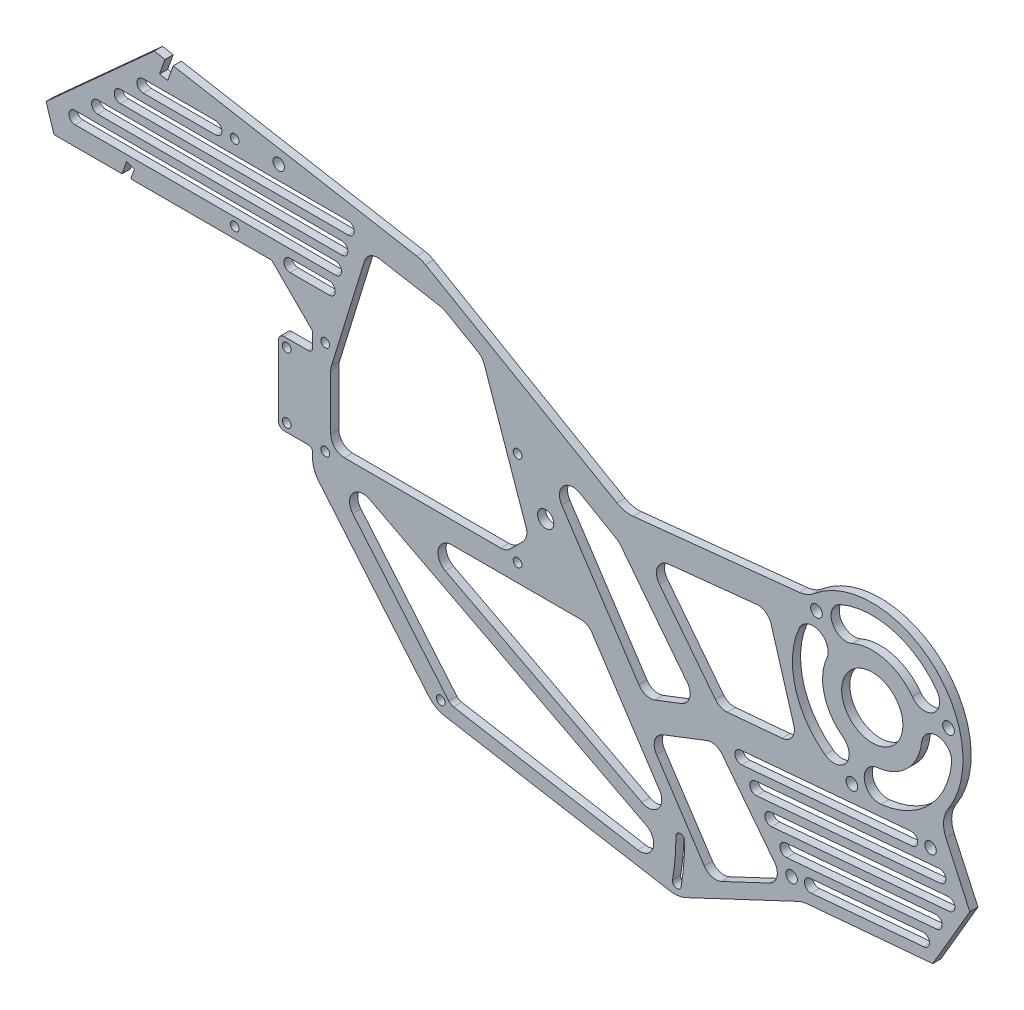
SolidWorks part; units mm, degrees
ref_plane "Front Plane" through (0, 0, 0) normal (0, 0, 1) x (1, 0, 0)
ref_plane "Top Plane" through (0, 0, 0) normal (0, 1, 0) x (1, 0, 0)
ref_plane "Right Plane" through (0, 0, 0) normal (1, 0, 0) x (0, 0, -1)
sketch "Sketch2" plane through (0, 0, 0) normal (0, 0, 1) x (1, 0, 0)
  line L0 (53.0727, 40.6) -> (-51.5431, 101) construction
  line L1 (53.0727, 40.6) -> (120.5529, 47.6) construction
  line L2 (53.0727, 40.6) -> (-21.5794, 83.7005)
  line L3 (53.0727, 40.6) -> (120.5529, 47.6)
  line L4 (-63.0431, 34) -> (-72.0431, 34) construction
  line L5 (-74.0431, 32) -> (-74.0431, 6) construction
  line L6 (-72.0431, 4) -> (-63.0431, 4) construction
  line L7 (-63.0431, 34) -> (-72.0431, 34)
  line L8 (-74.0431, 32) -> (-74.0431, 6)
  line L9 (-72.0431, 4) -> (-63.0431, 4)
  line L10 (-61.5431, 2.5) -> (-61.5431, -3) construction
  line L11 (-61.5431, 2.5) -> (-61.5431, -3)
  line L12 (-61.5431, 56) -> (-61.5431, 35.5) construction
  line L13 (-61.5431, 56) -> (-61.5431, 35.5)
  line L14 (-124.7453, 56) -> (-61.5431, 56) construction
  line L15 (-156.5431, 56) -> (-61.5431, 56)
  line L16 (-156.5431, 56) -> (-159.4878, 65.0628)
  line L17 (-159.4878, 65.0628) -> (-119.69, 101)
  line L18 (-119.69, 101) -> (-21.5794, 83.7005)
  line L19 (168.6964, 1.4596) -> (179.9678, -23.0752)
  line L20 (179.9678, -23.0752) -> (166.3352, -46.3808)
  line L22 (-124.7453, 56) -> (-127.69, 65.0628) construction
  line L23 (166.3352, -46.3808) -> (118.4161, -50.5732)
  line L24 (118.4161, -50.5732) -> (72.8599, -72.0315)
  line L25 (72.8599, -72.0315) -> (-16.548, -56.6231)
  line L26 (-16.548, -56.6231) -> (-61.5431, -3)
  line L27 (-51.5431, 101) -> (-119.69, 101) construction
  line L28 (-61.5431, -3) -> (-31.4636, -3) construction
  line L29 (73.5747, -52.93) -> (-14.4253, -52.93) construction
  line L33 (-42.7431, 62.05) -> (-42.7431, 39.5) construction
  line L34 (-41.9931, 62.8) -> (-1.0931, 62.8) construction
  line L35 (-0.3431, 62.05) -> (-0.3431, 39.5) construction
  line L36 (8.2869, 39.5) -> (-0.3431, 39.5) construction
  line L37 (-42.7431, 39.5) -> (-51.3731, 39.5) construction
  line L38 (-52.8731, 10) -> (-52.8731, 38) construction
  line L39 (9.7869, 10) -> (9.7869, 38) construction
  line L40 (8.2869, 8.5) -> (-51.3731, 8.5) construction
  line L41 (-42.7431, 62.05) -> (-42.7431, 39.5)
  line L42 (-41.9931, 62.8) -> (-1.0931, 62.8)
  line L43 (-0.3431, 62.05) -> (-0.3431, 39.5)
  line L44 (8.2869, 39.5) -> (-0.3431, 39.5)
  line L45 (-42.7431, 39.5) -> (-51.3731, 39.5)
  line L46 (-52.8731, 10) -> (-52.8731, 38)
  line L47 (9.7869, 10) -> (9.7869, 38)
  line L48 (8.2869, 8.5) -> (-51.3731, 8.5)
  arc A0 (177.4669, 23.9998) -> (120.5529, 47.6) centre (144.1169, 24) ccw construction
  arc A1 (168.6964, 1.4596) -> (120.5529, 47.6) centre (144.1169, 24) ccw
  arc A2 (-72.0431, 34) -> (-74.0431, 32) centre (-72.0431, 32) ccw construction
  arc A3 (-74.0431, 6) -> (-72.0431, 4) centre (-72.0431, 6) ccw construction
  arc A4 (-72.0431, 34) -> (-74.0431, 32) centre (-72.0431, 32) ccw
  arc A5 (-74.0431, 6) -> (-72.0431, 4) centre (-72.0431, 6) ccw
  arc A6 (-61.5431, 2.5) -> (-63.0431, 4) centre (-63.0431, 2.5) ccw construction
  arc A7 (-61.5431, 2.5) -> (-63.0431, 4) centre (-63.0431, 2.5) ccw
  arc A8 (-63.0431, 34) -> (-61.5431, 35.5) centre (-63.0431, 35.5) ccw construction
  arc A9 (-63.0431, 34) -> (-61.5431, 35.5) centre (-63.0431, 35.5) ccw
  circle A10 centre (-56.8731, 39.6) radius 1.6 construction
  circle A11 centre (13.7869, 39.6) radius 1.6 construction
  circle A12 centre (13.7869, 5) radius 1.6 construction
  circle A13 centre (-56.8731, 5) radius 1.6 construction
  circle A14 centre (-56.8731, 39.6) radius 1.6
  circle A15 centre (13.7869, 39.6) radius 1.6
  circle A16 centre (13.7869, 5) radius 1.6
  circle A17 centre (-56.8731, 5) radius 1.6
  circle A18 centre (-71.0431, 31) radius 1.6 construction
  circle A19 centre (-71.0431, 7) radius 1.6 construction
  circle A22 centre (24.1169, 24) radius 3 construction
  circle A23 centre (24.1169, 24) radius 3
  arc A24 (166.3088, -44.4468) -> (169.7736, -48.3119) centre (169.1616, -45.375) ccw construction
  arc A25 (-0.3431, 62.05) -> (-1.0931, 62.8) centre (-0.3431, 62.8) ccw construction
  arc A26 (-41.9931, 62.8) -> (-42.7431, 62.05) centre (-42.7431, 62.8) ccw construction
  arc A27 (-51.3731, 39.5) -> (-52.8731, 38) centre (-51.3731, 38) ccw construction
  circle A32 centre (123.6108, 44.5061) radius 2.15 construction
  circle A33 centre (172.1287, 31.5058) radius 2.15 construction
  circle A34 centre (136.6111, -4.0118) radius 2.15 construction
  circle A35 centre (123.6108, 44.5061) radius 2.15
  circle A36 centre (172.1287, 31.5058) radius 2.15
  circle A37 centre (136.6111, -4.0118) radius 2.15
  arc A38 (126.757, 0.3344) -> (133.3224, 9.2846) centre (130.0397, 4.8095) ccw construction
  arc A39 (127.4109, 31.3467) -> (133.3224, 9.2846) centre (144.1169, 24) ccw construction
  arc A40 (117.25, 35.8151) -> (126.757, 0.3344) centre (144.1169, 24) ccw construction
  arc A41 (127.4109, 31.3467) -> (117.25, 35.8151) centre (122.3305, 33.5809) ccw construction
  arc A42 (132.3018, 50.8668) -> (136.7702, 40.706) centre (134.536, 45.7864) ccw construction
  arc A43 (167.7824, 41.3598) -> (132.3018, 50.8668) centre (144.1169, 24) ccw construction
  arc A44 (158.8323, 34.7944) -> (136.7702, 40.706) centre (144.1169, 24) ccw construction
  arc A45 (158.8323, 34.7944) -> (167.7824, 41.3598) centre (163.3073, 38.0771) ccw construction
  circle A46 centre (144.1169, 24) radius 11.25 construction
  arc A47 (173.2918, 20.7987) -> (162.258, 22.0094) centre (167.7749, 21.4041) ccw construction
  arc A48 (146.1075, 5.8589) -> (162.258, 22.0094) centre (144.1169, 24) ccw construction
  arc A49 (147.3182, -5.1749) -> (173.2918, 20.7987) centre (144.1169, 24) ccw construction
  arc A50 (146.1075, 5.8589) -> (147.3182, -5.1749) centre (146.7128, 0.342) ccw construction
  arc A51 (126.757, 0.3344) -> (133.3224, 9.2846) centre (130.0397, 4.8095) ccw
  arc A52 (127.4109, 31.3467) -> (133.3224, 9.2846) centre (144.1169, 24) ccw
  arc A53 (117.25, 35.8151) -> (126.757, 0.3344) centre (144.1169, 24) ccw
  arc A54 (127.4109, 31.3467) -> (117.25, 35.8151) centre (122.3305, 33.5809) ccw
  arc A55 (132.3018, 50.8668) -> (136.7702, 40.706) centre (134.536, 45.7864) ccw
  arc A56 (167.7824, 41.3598) -> (132.3018, 50.8668) centre (144.1169, 24) ccw
  arc A57 (158.8323, 34.7944) -> (136.7702, 40.706) centre (144.1169, 24) ccw
  arc A58 (158.8323, 34.7944) -> (167.7824, 41.3598) centre (163.3073, 38.0771) ccw
  circle A59 centre (144.1169, 24) radius 11.25
  arc A60 (173.2918, 20.7987) -> (162.258, 22.0094) centre (167.7749, 21.4041) ccw
  arc A61 (146.1075, 5.8589) -> (162.258, 22.0094) centre (144.1169, 24) ccw
  arc A62 (147.3182, -5.1749) -> (173.2918, 20.7987) centre (144.1169, 24) ccw
  arc A63 (146.1075, 5.8589) -> (147.3182, -5.1749) centre (146.7128, 0.342) ccw
  circle A64 centre (-14.4253, -52.93) radius 1.6
  arc A65 (70.7196, -67.6037) -> (71.9747, -52.93) centre (-14.4253, -52.93) ccw
  arc A66 (73.8731, -68.1471) -> (75.1747, -52.93) centre (-14.4253, -52.93) ccw
  arc A67 (73.8731, -68.1471) -> (70.7196, -67.6037) centre (72.2963, -67.8754) cw
  arc A68 (75.1747, -52.93) -> (71.9747, -52.93) centre (73.5747, -52.93) ccw
  circle A69 centre (-71.0431, 31) radius 1.6
  circle A70 centre (-71.0431, 7) radius 1.6
  arc A71 (-52.8731, 10) -> (-51.3731, 8.5) centre (-51.3731, 10) ccw construction
  arc A72 (9.7869, 38) -> (8.2869, 39.5) centre (8.2869, 38) ccw construction
  arc A73 (8.2869, 8.5) -> (9.7869, 10) centre (8.2869, 10) ccw construction
  arc A74 (-0.3431, 62.05) -> (-1.0931, 62.8) centre (-0.3431, 62.8) ccw
  arc A75 (-41.9931, 62.8) -> (-42.7431, 62.05) centre (-42.7431, 62.8) ccw
  arc A76 (-51.3731, 39.5) -> (-52.8731, 38) centre (-51.3731, 38) ccw
  arc A77 (-52.8731, 10) -> (-51.3731, 8.5) centre (-51.3731, 10) ccw
  arc A78 (9.7869, 38) -> (8.2869, 39.5) centre (8.2869, 38) ccw
  arc A79 (8.2869, 8.5) -> (9.7869, 10) centre (8.2869, 10) ccw
  dimension "D3" = 1.6
  dimension "D6" = 3.2
  dimension "D7" = 4
  dimension "D8" = 4
  dimension "D1" = 88
  dimension "D2" = 15
  dimension "D4" = 95
  dimension "D5" = 10
  dimension "D9" = 4
  dimension "D10" = 4
  dimension "D11" = 50
  dimension "D12" = 70
  dimension "D13" = 35
  dimension "D14" = 5
  dimension "D15" = 27
  dimension "D16" = 55
extrude "Boss-Extrude1" add sketch "Sketch2" against normal blind 3
sketch "Sketch3" plane through (0, 0, 0) normal (0, 0, 1) x (1, 0, 0)
  line L0 (57.9603, -64.39) -> (-9.7599, -52.7193)
  line L1 (-11.5485, -51.6912) -> (-46.7716, -9.7139)
  line L2 (-40.6328, -2.0648) -> (61.1181, -55.0275)
  line L3 (-16.548, -56.6231) -> (72.8599, -72.0315) construction
  line L4 (-61.5431, -3) -> (-16.548, -56.6231) construction
  line L6 (65.9453, -41.3432) -> (41.192, -3.7503)
  line L7 (37.016, -1.5) -> (-10.4535, -1.5)
  line L8 (-12.7621, -10.9352) -> (59.4608, -48.5281)
  line L9 (-72.0431, 4) -> (-63.0431, 4) construction
  line L10 (11.0945, 7.9645) -> (15.7264, 12.5963)
  line L11 (16.9131, 17.7751) -> (1.5105, 62.0375)
  line L12 (-0.7118, 64.7243) -> (-12.7713, 71.6869)
  line L14 (-54.8731, 31.748) -> (-54.8731, 11.5)
  line L15 (-49.8731, 6.5) -> (7.559, 6.5)
  line L16 (88.7195, -59.0342) -> (106.3629, -50.7236)
  line L17 (108.1762, -43.1269) -> (88.9982, -18.5166)
  line L18 (83.255, -16.925) -> (67.1921, -23.1206)
  line L19 (64.8154, -30.5354) -> (82.4129, -57.2606)
  line L20 (64.3088, -13.5147) -> (74.0097, -9.7729)
  line L21 (76.1542, -2.0345) -> (51.5925, 29.4845)
  line L22 (50.1486, 30.7413) -> (36.6662, 38.5253)
  line L23 (29.9902, 31.4455) -> (58.3334, -11.5994)
  line L24 (110.9315, -2.3425) -> (90.802, -4.1036)
  line L25 (86.4223, -2.196) -> (65.8664, 24.1824)
  line L26 (69.2945, 32.2291) -> (101.6316, 35.5836)
  line L27 (106.9405, 32.0339) -> (115.4276, 3.4604)
  line L28 (72.8599, -72.0315) -> (118.4161, -50.5732) construction
  line L29 (118.4161, -50.5732) -> (166.3352, -46.3808) construction
  line L30 (-51.3731, 8.5) -> (8.2869, 8.5) construction
  line L31 (-52.8731, 38) -> (-52.8731, 10) construction
  line L32 (-14.4031, 72.2808) -> (-36.8286, 76.235)
  line L33 (-42.4757, 72.7818) -> (-54.6519, 33.2187)
  line L34 (53.0727, 40.6) -> (-21.5794, 83.7005) construction
  line L35 (-21.5794, 83.7005) -> (-119.69, 101) construction
  line L36 (120.5529, 47.6) -> (53.0727, 40.6) construction
  line L37 (162.8894, -40.3884) -> (121.4652, -44.0125) construction
  line L38 (163.0872, -42.6497) -> (121.663, -46.2738)
  line L39 (162.6915, -38.1271) -> (121.2673, -41.7512)
  line L40 (167.5555, -32.4114) -> (112.4569, -37.2319) construction
  line L41 (167.7533, -34.6728) -> (112.6547, -39.4933)
  line L42 (167.3576, -30.1501) -> (112.2591, -34.9706)
  line L43 (172.2216, -24.4345) -> (106.9353, -30.1463) construction
  line L44 (172.4194, -26.6958) -> (107.1332, -32.4076)
  line L45 (172.0237, -22.1732) -> (106.7375, -27.885)
  line L46 (168.8788, -17.1583) -> (101.4137, -23.0607) construction
  line L47 (169.0766, -19.4196) -> (101.6116, -25.322)
  line L48 (168.681, -14.897) -> (101.2159, -20.7994)
  line L49 (142.1773, -42.2004) -> (141.5201, -34.6892) construction
  line L50 (141.5201, -34.6892) -> (140.863, -27.1781) construction
  line L51 (140.863, -27.1781) -> (140.2058, -19.6669) construction
  line L52 (166.3352, -46.3808) -> (179.9678, -23.0752) construction
  line L53 (112.4569, -37.2319) -> (101.4137, -23.0607) construction
  line L54 (106.9353, -30.1463) -> (101.4138, -34.449) construction
  line L55 (158.5627, -10.4922) -> (95.8921, -15.9751) construction
  line L56 (158.7605, -12.7535) -> (96.09, -18.2364)
  line L57 (158.3648, -8.2309) -> (95.6943, -13.7138)
  line L58 (140.2058, -19.6669) -> (139.5487, -12.1557) construction
  line L59 (-10.4535, -6.5) -> (-42.9414, -6.5) construction
  line L60 (121.4652, -44.0125) -> (114.4918, -44.6226) construction
  line L61 (165.536, -9.8821) -> (172.2216, -24.4345) construction
  line L62 (179.9678, -23.0752) -> (168.6964, 1.4596) construction
  line L63 (104.1746, -32.2977) -> (118.4161, -50.5732) construction
  arc A0 (9.7869, 38) -> (8.2869, 39.5) centre (8.2869, 38) ccw construction
  arc A1 (-0.3431, 62.05) -> (-1.0931, 62.8) centre (-0.3431, 62.8) ccw construction
  circle A2 centre (13.7869, 5) radius 1.6 construction
  circle A3 centre (-56.8731, 39.6) radius 1.6 construction
  arc A5 (117.25, 35.8151) -> (126.757, 0.3344) centre (144.1169, 24) ccw construction
  arc A6 (61.1181, -55.0275) -> (57.9603, -64.39) centre (58.8095, -59.4627) cw
  arc A7 (163.0872, -42.6497) -> (162.6915, -38.1271) centre (162.8894, -40.3884) ccw
  arc A8 (121.2673, -41.7512) -> (121.663, -46.2738) centre (121.4652, -44.0125) ccw
  arc A9 (167.7533, -34.6728) -> (167.3576, -30.1501) centre (167.5555, -32.4114) ccw
  arc A10 (112.2591, -34.9706) -> (112.6547, -39.4933) centre (112.4569, -37.2319) ccw
  arc A11 (172.4194, -26.6958) -> (172.0237, -22.1732) centre (172.2216, -24.4345) ccw
  arc A12 (106.7375, -27.885) -> (107.1332, -32.4076) centre (106.9353, -30.1463) ccw
  arc A13 (169.0766, -19.4196) -> (168.681, -14.897) centre (168.8788, -17.1583) ccw
  arc A14 (101.2159, -20.7994) -> (101.6116, -25.322) centre (101.4137, -23.0607) ccw
  arc A15 (65.9453, -41.3432) -> (59.4608, -48.5281) centre (61.7693, -44.0929) cw
  arc A16 (158.7605, -12.7535) -> (158.3648, -8.2309) centre (158.5627, -10.4922) ccw
  arc A17 (95.6943, -13.7138) -> (96.09, -18.2364) centre (95.8921, -15.9751) ccw
  arc A18 (168.6964, 1.4596) -> (120.5529, 47.6) centre (144.1169, 24) ccw construction
  circle A19 centre (165.536, -9.8821) radius 2.1
  circle A20 centre (24.1169, 24) radius 3 construction
  arc A21 (-54.8731, 11.5) -> (-49.8731, 6.5) centre (-49.8731, 11.5) ccw
  arc A22 (-54.6519, 33.2187) -> (-54.8731, 31.748) centre (-49.8731, 31.748) ccw
  arc A23 (-36.8286, 76.235) -> (-42.4757, 72.7818) centre (-37.6969, 71.311) ccw
  arc A24 (-12.7713, 71.6869) -> (-14.4031, 72.2808) centre (-15.2713, 67.3568) ccw
  arc A25 (1.5105, 62.0375) -> (-0.7118, 64.7243) centre (-3.2118, 60.3942) ccw
  arc A26 (15.7264, 12.5963) -> (16.9131, 17.7751) centre (12.1908, 16.1318) ccw
  arc A27 (11.0945, 7.9645) -> (7.559, 6.5) centre (7.559, 11.5) cw
  arc A43 (-9.7599, -52.7193) -> (-11.5485, -51.6912) centre (-9.2504, -49.7628) cw
  circle A47 centre (114.4918, -44.6226) radius 2.1
  arc A48 (-12.7621, -10.9352) -> (-10.4535, -1.5) centre (-10.4535, -6.5) cw
  arc A49 (-46.7716, -9.7139) -> (-40.6328, -2.0648) centre (-42.9414, -6.5) cw
  arc A50 (106.3629, -50.7236) -> (108.1762, -43.1269) centre (104.2323, -46.2003) ccw
  arc A51 (88.7195, -59.0342) -> (82.4129, -57.2606) centre (86.5889, -54.5109) cw
  arc A52 (67.1921, -23.1206) -> (64.8154, -30.5354) centre (68.9914, -27.7856) ccw
  arc A53 (83.255, -16.925) -> (88.9982, -18.5166) centre (85.0543, -21.59) cw
  arc A54 (86.4223, -2.196) -> (90.802, -4.1036) centre (90.3662, 0.8773) ccw
  arc A55 (110.9315, -2.3425) -> (115.4276, 3.4604) centre (110.4957, 2.6384) ccw
  arc A56 (101.6316, 35.5836) -> (106.9405, 32.0339) centre (102.1475, 30.6102) cw
  arc A57 (69.2945, 32.2291) -> (65.8664, 24.1824) centre (69.8104, 27.2558) ccw
  arc A58 (74.0097, -9.7729) -> (76.1542, -2.0345) centre (72.2103, -5.1079) ccw
  arc A59 (37.016, -1.5) -> (41.192, -3.7503) centre (37.016, -6.5) cw
  arc A60 (58.3334, -11.5994) -> (64.3088, -13.5147) centre (62.5094, -8.8496) ccw
  arc A61 (50.1486, 30.7413) -> (51.5925, 29.4845) centre (47.6486, 26.4111) cw
  arc A62 (36.6662, 38.5253) -> (29.9902, 31.4455) centre (34.1662, 34.1952) ccw
  arc A63 (75.1747, -52.93) -> (71.9747, -52.93) centre (73.5747, -52.93) ccw construction
  point P7 (117.9785, -44.3176)
  point P42 (142.1773, -42.2004)
  point P55 (140.0062, -34.8217)
  point P69 (139.5784, -27.2904)
  point P80 (135.1463, -20.1095)
  point P97 (127.2274, -13.2336)
  point P126 (-54.8731, 6.5)
  point P129 (-54.8731, 32.5)
  point P148 (88.0935, -4.3406)
  point P150 (88.0935, -4.3406)
  point P177 (0, 0)
  point P178 (57.9116, -1.5)
  point P179 (0, 0)
  point P180 (62.7397, -10.3041)
  point P181 (76.1542, -2.196)
  dimension "D11" = 4
  dimension "D12" = 4
  dimension "D21" = 33.35
  dimension "D26" = 6
  dimension "D29" = 4.2
  dimension "D30" = 7
  dimension "D34" = 5
  dimension "D35" = 5
  dimension "D36" = 5
  dimension "D37" = 5
  dimension "D38" = 5
  dimension "D39" = 5
  dimension "D40" = 5
  dimension "D41" = 5
  dimension "D42" = 5
  dimension "D56" = 3
  dimension "D59" = 4.2
  dimension "D27" = 5
  dimension "D1" = 5
  dimension "D2" = 7
  dimension "D3" = 5
  dimension "D4" = 8
  dimension "D5" = 2
  dimension "D6" = 2
  dimension "D7" = 10
  dimension "D8" = 6
  dimension "D9" = 45
  dimension "D10" = 1.5
  dimension "D13" = 26
  dimension "D14" = 10
  dimension "D15" = 10
  dimension "D16" = 10
  dimension "D17" = 5
  dimension "D18" = 5
  dimension "D19" = 10
  dimension "D20" = 8
  dimension "D22" = 6
  dimension "D23" = 6
  dimension "D24" = 4
  dimension "D25" = 3
  dimension "D31" = 7
  dimension "D32" = 10
  dimension "D33" = 9
  dimension "D60" = 7
extrude "Cut-Extrude1" cut sketch "Sketch3" against normal blind 3
chamfer "Chamfer1" distance 15 angle 45 1 edges at (-61.5431, 56, -1.5)
sketch "Sketch4" plane through (0, 0, 0) normal (0, 0, 1) x (1, 0, 0)
  line L0 (-53.1579, 65.2699) -> (-148.8136, 65.2699) construction
  line L1 (-53.1579, 63) -> (-148.8136, 63)
  line L2 (-53.1579, 67.5399) -> (-148.8136, 67.5399)
  line L3 (-50.8404, 72.7999) -> (-140.4747, 72.7999) construction
  line L4 (-50.8404, 70.53) -> (-140.4747, 70.53)
  line L5 (-50.8404, 75.0699) -> (-140.4747, 75.0699)
  line L6 (-48.5229, 80.3299) -> (-132.1358, 80.3299) construction
  line L7 (-48.5229, 78.06) -> (-132.1358, 78.06)
  line L8 (-48.5229, 82.5999) -> (-132.1358, 82.5999)
  line L9 (-97.1496, 87.8599) -> (-123.7969, 87.8599) construction
  line L10 (-97.1496, 85.59) -> (-123.7969, 85.59)
  line L11 (-97.1496, 90.1299) -> (-123.7969, 90.1299)
  line L12 (-53.1579, 65.2699) -> (-48.5229, 80.3299) construction
  line L13 (-42.4757, 72.7818) -> (-54.6519, 33.2187) construction
  line L14 (-110.4732, 65.2699) -> (-110.4732, 72.7999) construction
  line L15 (-110.4732, 72.7999) -> (-110.4732, 80.3299) construction
  line L16 (-110.4732, 80.3299) -> (-110.4732, 87.8599) construction
  line L17 (-156.5431, 56) -> (-76.5431, 56) construction
  line L18 (-21.5794, 83.7005) -> (-119.69, 101) construction
  line L20 (-119.69, 101) -> (-159.4878, 65.0628) construction
  line L25 (-128.3582, 56) -> (-127.0152, 59.7678)
  line L26 (-127.0152, 59.7678) -> (-129.8411, 60.7751)
  line L27 (-129.8411, 60.7751) -> (-131.5431, 56)
  line L28 (-131.5431, 56) -> (-128.3582, 56)
  line L29 (-112.7542, 99.777) -> (-114.7687, 94.1253)
  line L30 (-114.7687, 94.1253) -> (-117.7653, 94.6537)
  line L31 (-117.7653, 94.6537) -> (-115.7508, 100.3054)
  line L32 (-115.7508, 100.3054) -> (-112.7542, 99.777)
  line L33 (-90.1496, 60) -> (-90.1496, 87.8599) construction
  line L34 (-55.4754, 57.7399) -> (-69.7978, 57.7399) construction
  line L35 (-55.4754, 55.47) -> (-69.7978, 55.47)
  line L36 (-55.4754, 60.0099) -> (-69.7978, 60.0099)
  line L37 (-76.5431, 56) -> (-61.5431, 41) construction
  line L38 (-64.3393, 57.7399) -> (-64.3393, 65.2699) construction
  arc A0 (-53.1579, 63) -> (-53.1579, 67.5399) centre (-53.1579, 65.2699) ccw
  arc A1 (-148.8136, 67.5399) -> (-148.8136, 63) centre (-148.8136, 65.2699) ccw
  arc A2 (-50.8404, 70.53) -> (-50.8404, 75.0699) centre (-50.8404, 72.7999) ccw
  arc A3 (-140.4747, 75.0699) -> (-140.4747, 70.53) centre (-140.4747, 72.7999) ccw
  arc A4 (-48.5229, 78.06) -> (-48.5229, 82.5999) centre (-48.5229, 80.3299) ccw
  arc A5 (-132.1358, 82.5999) -> (-132.1358, 78.06) centre (-132.1358, 80.3299) ccw
  arc A6 (-97.1496, 85.59) -> (-97.1496, 90.1299) centre (-97.1496, 87.8599) ccw
  arc A7 (-123.7969, 90.1299) -> (-123.7969, 85.59) centre (-123.7969, 87.8599) ccw
  arc A8 (121.2673, -41.7512) -> (121.663, -46.2738) centre (121.4652, -44.0125) ccw construction
  circle A9 centre (-73.9629, 87.8599) radius 2.1
  circle A10 centre (-90.1496, 87.8599) radius 1.6
  circle A11 centre (-90.1496, 60) radius 1.6
  arc A12 (-55.4754, 55.47) -> (-55.4754, 60.0099) centre (-55.4754, 57.7399) ccw
  arc A13 (-69.7978, 60.0099) -> (-69.7978, 55.47) centre (-69.7978, 57.7399) ccw
  point P2 (-100.9857, 65.2699)
  point P7 (-95.6575, 72.7999)
  point P14 (-90.3293, 80.3299)
  point P21 (-110.4732, 87.8599)
  point P58 (-62.6366, 57.7399)
  dimension "D2" = 4.2
  dimension "D11" = 3.2
  dimension "D13" = 5
  dimension "D14" = 4
  dimension "D1" = 7
  dimension "D3" = 7
  dimension "D4" = 7
  dimension "D5" = 7
  dimension "D6" = 7
  dimension "D7" = 8
  dimension "D8" = 3
  dimension "D9" = 4
  dimension "D10" = 6
  dimension "D12" = 7.53
  dimension "D15" = 50
  dimension "D16" = 7
  dimension "D17" = 4
  dimension "D18" = 25
  dimension "D19" = 6
extrude "Cut-Extrude2" cut sketch "Sketch4" against normal blind 3
fillet "Fillet1" radius 10 8 edges at (53.0727, 40.6, -1.5) (120.5529, 47.6, -1.5) (168.6964, 1.4596, -1.5) (-61.5431, -3, -1.5) (-16.548, -56.6231, -1.5) (72.8599, -72.0315, -1.5) (118.4161, -50.5732, -1.5) (-21.5794, 83.7005, -1.5)
